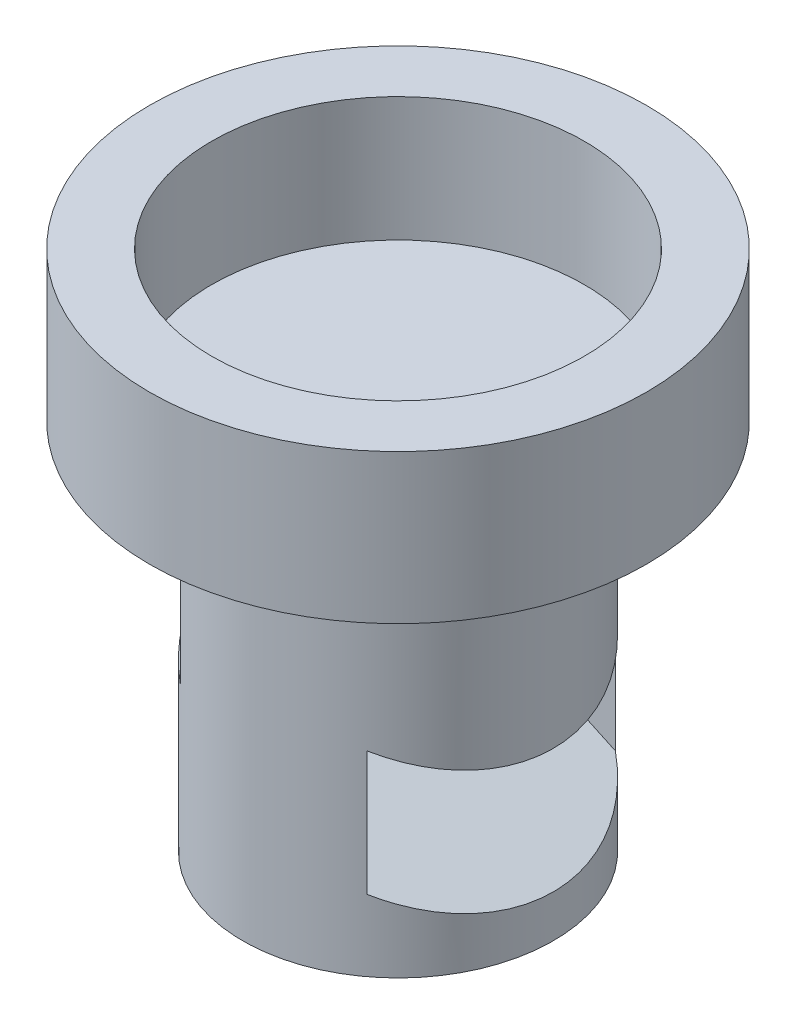
SolidWorks part; units mm, degrees
ref_plane "Alzado" through (0, 0, 0) normal (0, 0, 1) x (1, 0, 0)
ref_plane "Planta" through (0, 0, 0) normal (0, 1, 0) x (1, 0, 0)
ref_plane "Vista lateral" through (0, 0, 0) normal (1, 0, 0) x (0, 0, -1)
sketch "Croquis1" plane through (0, 0, 0) normal (0, 1, 0) x (1, 0, 0)
  circle A0 centre (0, 0) radius 15
  circle A1 centre (0, 0) radius 20
  dimension "D1" = 30
  dimension "D2" = 40
extrude "Saliente-Extruir1" add sketch "Croquis1" against normal blind 10
sketch "Croquis2" plane through (0, -10, 0) normal (0, -1, 0) x (1, 0, 0)
  circle A0 centre (0, 0) radius 20
extrude "Saliente-Extruir2" add sketch "Croquis2" along normal blind 2
sketch "Croquis3" plane through (0, -12, 0) normal (0, -1, 0) x (1, 0, 0)
  circle A0 centre (0, 0) radius 12.5
  dimension "D1" = 25
extrude "Saliente-Extruir3" add sketch "Croquis3" along normal blind 30
sketch "Croquis4" plane through (0, 0, 0) normal (0, 0, 1) x (1, 0, 0)
  line L0 (-15.5461, -15.5108) -> (-15.5461, -25.5108)
  line L2 (-15.5461, -25.5108) -> (14.4539, -39.5)
  line L4 (14.4539, -39.5) -> (14.4539, -29.5)
  line L5 (14.4539, -29.5) -> (-15.5461, -15.5108)
  line L6 (-12.5, -42) -> (12.5, -42) construction
  dimension "D1" = 10
  dimension "D2" = 10
  dimension "D3" = 25
  dimension "D4" = 30
  dimension "D5" = 2.5
extrude "Cortar-Extruir2" cut sketch "Croquis4" against normal mid plane 20
